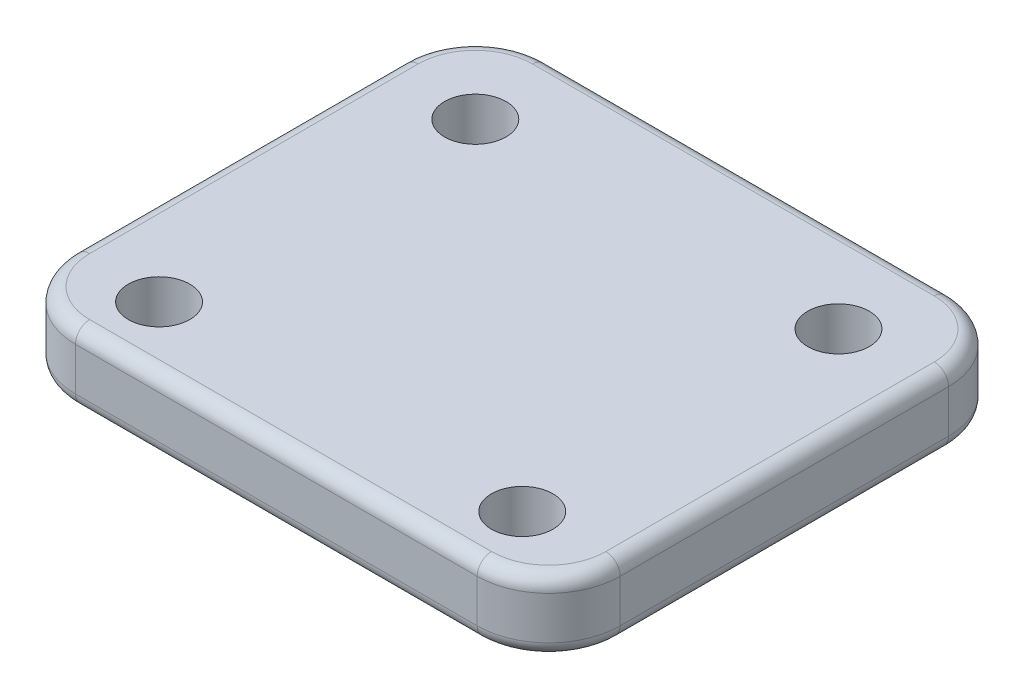
SolidWorks part; units mm, degrees
ref_plane "Front Plane" through (0, 0, 0) normal (0, 0, 1) x (1, 0, 0)
ref_plane "Top Plane" through (0, 0, 0) normal (0, 1, 0) x (1, 0, 0)
ref_plane "Right Plane" through (0, 0, 0) normal (1, 0, 0) x (0, 0, -1)
sketch "Sketch1" plane through (0, 0, 0) normal (0, 1, 0) x (1, 0, 0)
  line L0 (0, -13.97) -> (38.1, -13.97) construction
  line L1 (0, 0) -> (38.1, 0)
  line L2 (0, 0) -> (0, -32.97)
  line L3 (0, -32.97) -> (38.1, -32.97)
  line L4 (38.1, 0) -> (38.1, -32.97)
  line L5 (0, -23.97) -> (38.1, -23.97) construction
  line L6 (0, -6.35) -> (38.1, -6.35) construction
  line L7 (6.35, -6.35) -> (31.75, -6.35) construction
  line L8 (0, -28.47) -> (38.1, -28.47) construction
  circle A3 centre (6.35, -6.35) radius 2.15
  circle A4 centre (31.75, -6.35) radius 2.15
  circle A5 centre (31.75, -28.47) radius 2.15
  circle A6 centre (6.35, -28.47) radius 2.15
  point P23 (0, 0)
  point P24 (0, 0)
  dimension "D6" = 4.3
  dimension "D1" = 10
  dimension "D2" = 13.97
  dimension "D3" = 9
  dimension "D4" = 38.1
  dimension "D5" = 6.35
  dimension "D7" = 6.35
  dimension "D10" = 25.4
  dimension "D11" = 4.5
  dimension "D8" = 2
  dimension "D9" = 2
extrude "Boss-Extrude1" add sketch "Sketch1" along normal blind 5
fillet "Fillet1" radius 5 4 edges at (0, 2.5, 0) (38.1, 2.5, 0) (38.1, 2.5, 32.97) (0, 2.5, 32.97)
fillet "Fillet2" radius 1 16 edges at (1.4645, 0, 31.5055) (0, 0, 16.485) (1.4645, 0, 1.4645) (19.05, 0, 0) (36.6355, 0, 1.4645) (38.1, 0, 16.485) (36.6355, 0, 31.5055) (1.4645, 5, 31.5055) (0, 5, 16.485) (1.4645, 5, 1.4645) (19.05, 5, 0) (36.6355, 5, 1.4645) (38.1, 5, 16.485) (36.6355, 5, 31.5055) (19.05, 0, 32.97) (19.05, 5, 32.97)
